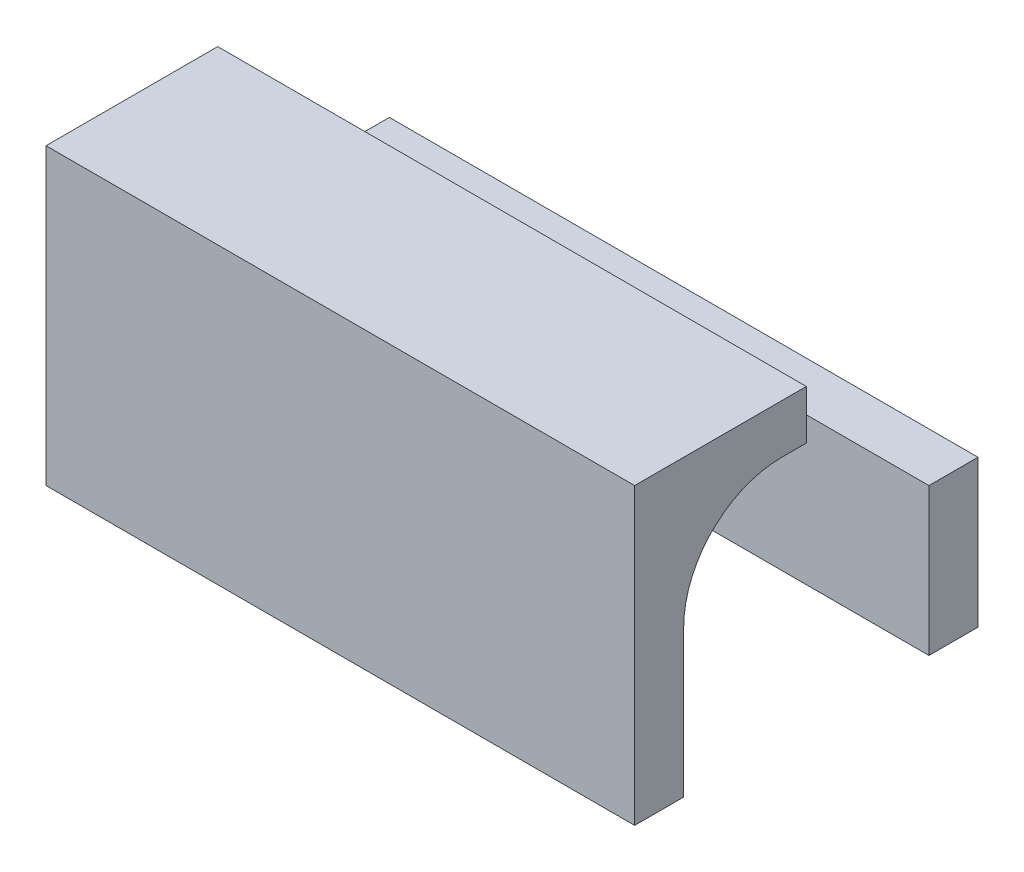
SolidWorks part; units mm, degrees
ref_plane "Front Plane" through (0, 0, 0) normal (0, 0, 1) x (1, 0, 0)
ref_plane "Top Plane" through (0, 0, 0) normal (0, 1, 0) x (1, 0, 0)
ref_plane "Right Plane" through (0, 0, 0) normal (1, 0, 0) x (0, 0, -1)
sketch "Sketch1" plane through (0, 0, 0) normal (1, 0, 0) x (0, 0, -1)
  line L0 (6000, 0) -> (7000, 0)
  line L1 (0, 0) -> (1000, 0)
  line L2 (0, 0) -> (0, 6000)
  line L3 (0, 6000) -> (3500, 6000)
  line L4 (7000, 0) -> (7000, 3000)
  line L6 (1000, 0) -> (1000, 3000)
  line L7 (3000, 5000) -> (3500, 5000)
  line L8 (6000, 0) -> (6000, 3000)
  line L9 (3500, 5000) -> (3500, 6000)
  line L10 (7000, 3000) -> (6000, 3000)
  arc A0 (3000, 5000) -> (1000, 3000) centre (3000, 3000) ccw
  point P11 (1000, 5000)
  point P14 (6000, 5000)
  dimension "D6" = 2000
  dimension "D3" = 5000
  dimension "D4" = 5000
  dimension "D5" = 1000
extrude "Boss-Extrude1" add sketch "Sketch1" along normal blind 12000 contours L2 L3 L9 L7 A0 L6 L1 | L0 L4 L10 L8
